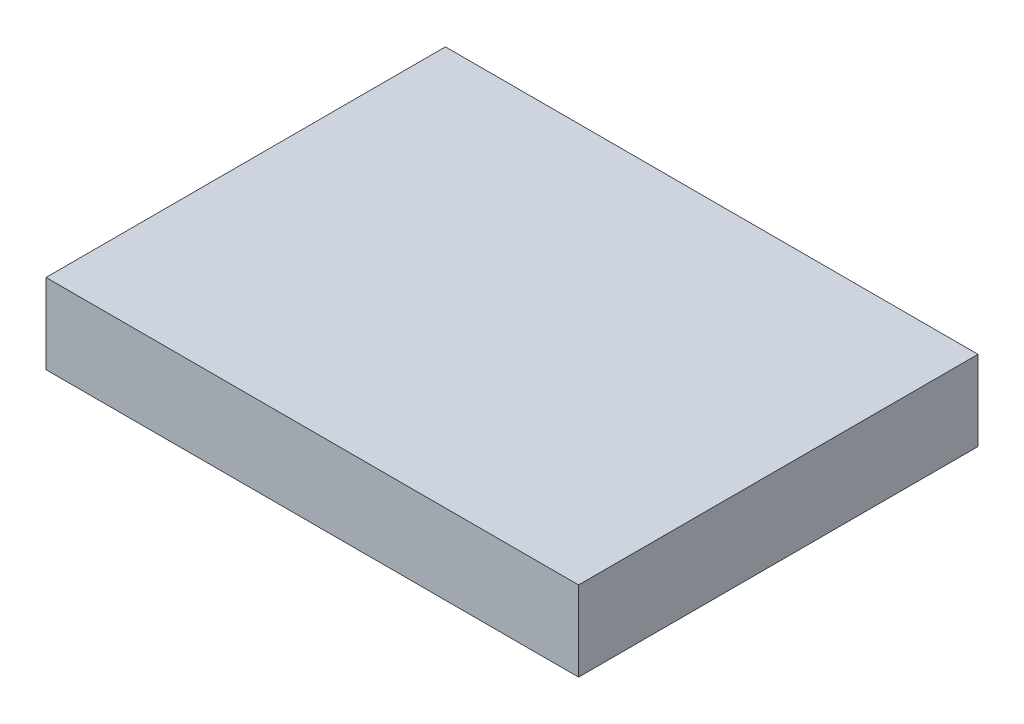
SolidWorks part; units mm, degrees
ref_plane "Front Plane" through (0, 0, 0) normal (0, 0, 1) x (1, 0, 0)
ref_plane "Top Plane" through (0, 0, 0) normal (0, 1, 0) x (1, 0, 0)
ref_plane "Right Plane" through (0, 0, 0) normal (1, 0, 0) x (0, 0, -1)
sketch "Sketch1" plane through (0, 0, 0) normal (0, 1, 0) x (1, 0, 0)
  line L1 (0, 0) -> (50.8, 0)
  line L2 (0, 0) -> (0, 38.1)
  line L3 (0, 38.1) -> (50.8, 38.1)
  line L4 (50.8, 0) -> (50.8, 38.1)
  dimension "D1" = 50.8
  dimension "D2" = 38.1
extrude "Boss-Extrude1" add sketch "Sketch1" along normal blind 7.62
